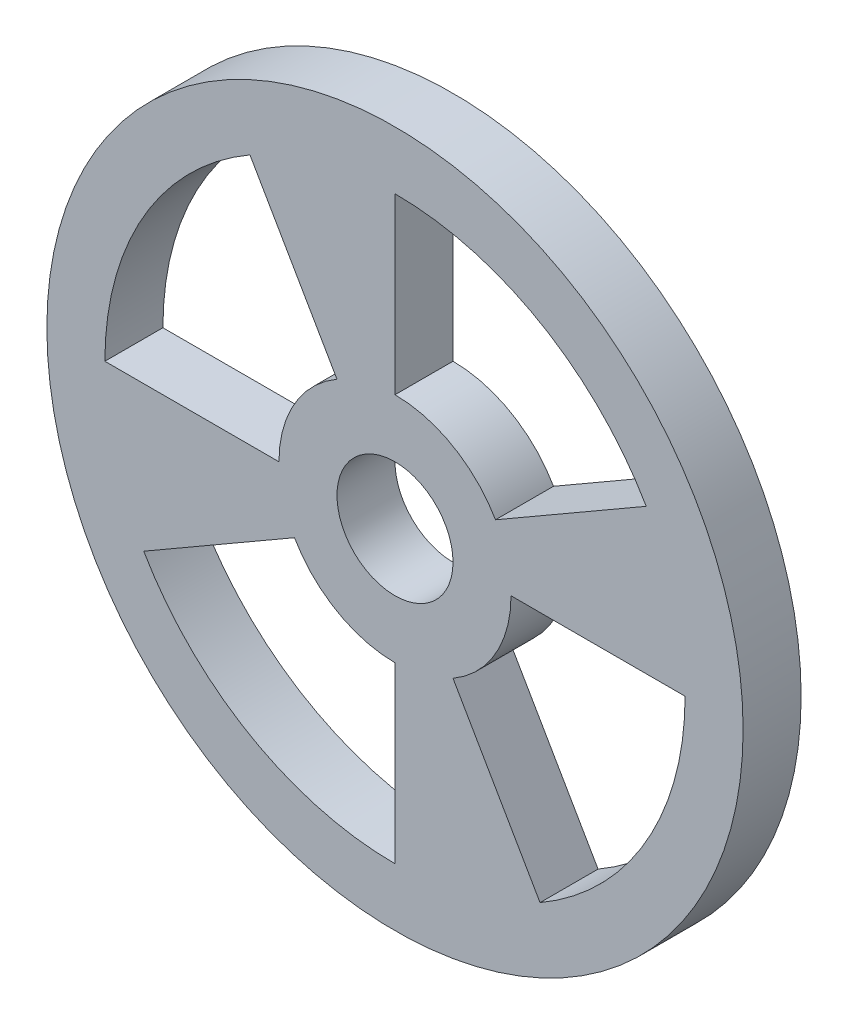
SolidWorks part; units mm, degrees
ref_plane "前视基准面" through (0, 0, 0) normal (0, 0, 1) x (1, 0, 0)
ref_plane "上视基准面" through (0, 0, 0) normal (0, 1, 0) x (1, 0, 0)
ref_plane "右视基准面" through (0, 0, 0) normal (1, 0, 0) x (0, 0, -1)
sketch "草图1" plane through (0, 0, 0) normal (0, 0, 1) x (1, 0, 0)
  circle A0 centre (0, 0) radius 60
  circle A1 centre (0, 0) radius 10
extrude "凸台-拉伸1" add sketch "草图1" along normal blind 10
sketch "草图2" plane through (0, 0, 0) normal (0, 0, 1) x (1, 0, 0)
  line L0 (0, 50) -> (0, 20)
  line L1 (17.3205, 10) -> (43.3013, 25)
  arc A0 (43.3013, 25) -> (0, 50) centre (0, 0) ccw
  arc A1 (0, 20) -> (17.3205, 10) centre (0, 0) cw
extrude "切除-拉伸1" cut sketch "草图2" against normal mid plane 242
ref_axis "基准轴1" through (0, 0, 10.5) along (0, 0, -1)
pattern_circular "阵列(圆周)1" count 4 over 360 about axis through (0, 0, 10.5) along (0, 0, -1) of "切除-拉伸1"
